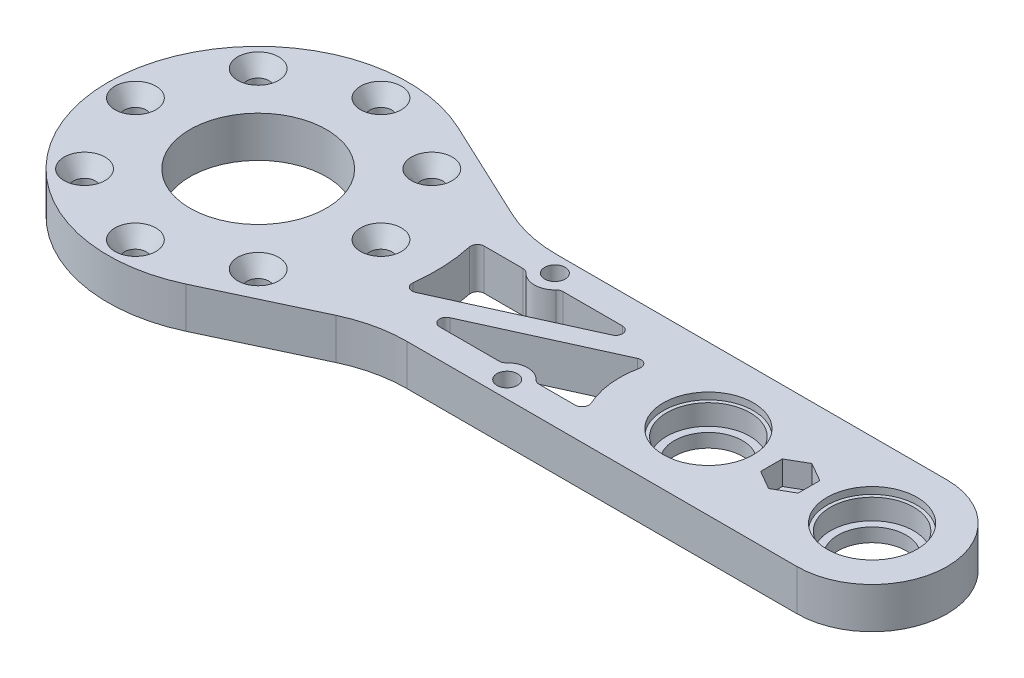
SolidWorks part; units mm, degrees
material "ABS"
ref_plane "前视基准面" through (0, 0, 0) normal (0, 0, 1) x (1, 0, 0)
ref_plane "上视基准面" through (0, 0, 0) normal (0, 1, 0) x (1, 0, 0)
ref_plane "右视基准面" through (0, 0, 0) normal (1, 0, 0) x (0, 0, -1)
other "Configuration Table"
sketch "草图1" plane through (0, 0, 0) normal (0, 1, 0) x (1, 0, 0)
  line L0 (0, 0) -> (-100, 0) construction
  line L1 (-100, -18) -> (-100, 18) construction
  line L2 (-10, -11) -> (-80.9474, -11)
  line L3 (-10, -11) -> (-10, 11) construction
  line L5 (-10, 11) -> (-80.9474, 11)
  line L7 (-74.8942, -6.76) -> (-45.1042, -6.76)
  line L12 (-74.8942, 6.76) -> (-45.1042, 6.76)
  line L13 (-74.8942, -6.76) -> (-45.1042, 6.76) construction
  line L14 (-74.2743, -8.1259) -> (-44.4843, 5.3941)
  line L15 (-75.5141, -5.3941) -> (-45.7241, 8.1259)
  circle A0 centre (-10, 0) radius 5
  circle A1 centre (-34, 0) radius 5
  circle A2 centre (-34, 0) radius 5 construction
  arc A3 (-5, 0) -> (-15, 0) centre (-10, 0) ccw construction
  circle A4 centre (-100, 0) radius 22
  circle A5 centre (-100, 0) radius 18 construction
  circle A6 centre (-100, 18) radius 1.6
  circle A7 centre (-87.2721, 12.7279) radius 1.6
  circle A8 centre (-82, 0) radius 1.6
  circle A9 centre (-87.2721, -12.7279) radius 1.6
  circle A10 centre (-100, -18) radius 1.6
  circle A11 centre (-112.7279, -12.7279) radius 1.6
  circle A12 centre (-118, 0) radius 1.6
  circle A13 centre (-112.7279, 12.7279) radius 1.6
  circle A14 centre (-100, 0) radius 10
  circle A15 centre (-34, 0) radius 9 construction
  arc A16 (-10, -11) -> (-10, 11) centre (-10, 0) ccw
  arc A20 (-74.8942, -6.76) -> (-74.8942, 6.76) centre (-100, 0) ccw
  arc A21 (-45.1042, 6.76) -> (-45.1042, -6.76) centre (-34, 0) ccw
  point P8 (-50, 0)
  point P31 (-100, 0)
  dimension "D2" = 10
  dimension "D3" = 10
  dimension "D4" = 24
  dimension "D6" = 44
  dimension "D7" = 36
  dimension "D8" = 3.2
  dimension "D10" = 20
  dimension "D11" = 18
  dimension "D12" = 22
  dimension "D13" = 50
  dimension "D14" = 4.24
  dimension "D15" = 4.24
  dimension "D16" = 52
  dimension "D17" = 26
  dimension "D18" = 1.5
  dimension "D1" = 100
  dimension "D5" = 10
  dimension "D19" = 1.5
  dimension "D9" = 8
extrude "凸台-拉伸1" add sketch "草图1" along normal blind 6
fillet "圆角1" radius 20 2 edges at (-80.9474, 3, -11) (-80.9474, 3, 11)
fillet "圆角2" radius 1 6 edges at (-45.1042, 3, 6.76) (-46.1433, 3, -4.6411) (-71.2646, 3, 6.76) (-74.8942, 3, -6.76) (-48.7337, 3, -6.76) (-74.4698, 3, 4.9201)
sketch "草图2" plane through (0, 0, 0) normal (0, -1, 0) x (1, 0, 0)
  circle A0 centre (-34, 0) radius 6.6
  circle A1 centre (-10, 0) radius 6.6
  dimension "D1" = 13.2
extrude "切除-拉伸2" cut sketch "草图2" along normal blind 5 from surface at -6 starting at face at (-53.6395, 6, 2.9007)
sketch "草图3" plane through (0, 6, 0) normal (0, 1, 0) x (1, 0, 0)
  line L0 (-10, 0) -> (-65, 0) construction
  line L1 (-65, 0) -> (-65, 8.5) construction
  line L2 (-65, 0) -> (-65, -8.5) construction
  line L3 (-73.6216, 6.76) -> (-53.3568, 6.76) construction
  line L4 (-57.4438, 6.76) -> (-52.5562, 6.76) construction
  circle A0 centre (-65, 8.5) radius 1.5
  circle A1 centre (-65, -8.5) radius 1.5 construction
  circle A2 centre (-55, 8.5) radius 1.5 construction
  arc A3 (-57.4438, 6.76) -> (-52.5562, 6.76) centre (-55, 8.5) ccw construction
  circle A4 centre (-55, -8.5) radius 1.5
  dimension "D3" = 8.5
  dimension "D5" = 2
  dimension "D4" = 3
  dimension "D7" = 6
  dimension "D1" = 55
  dimension "D2" = 8.5
  dimension "D6" = 10
extrude "切除-拉伸3" cut sketch "草图3" against normal blind 34
sketch "草图4" plane through (0, 6, 0) normal (0, 1, 0) x (1, 0, 0)
  line L0 (-71.6627, 11) -> (-90.6504, 19.9145)
  line L1 (-71.6627, -11) -> (-90.6504, -19.9145)
  arc A0 (-85.1567, 16.2381) -> (-85.1567, -16.2381) centre (-100, 0) ccw construction
  arc A1 (-85.1567, 16.2381) -> (-71.6627, 11) centre (-71.6627, 31) ccw construction
  arc A2 (-85.1567, 16.2381) -> (-90.6504, 19.9145) centre (-100, 0) ccw
  arc A3 (-85.1567, 16.2381) -> (-71.6627, 11) centre (-71.6627, 31) ccw
  arc A4 (-71.6627, -11) -> (-85.1567, -16.2381) centre (-71.6627, -31) ccw construction
  arc A5 (-71.6627, -11) -> (-85.1567, -16.2381) centre (-71.6627, -31) ccw
  arc A6 (-90.6504, -19.9145) -> (-85.1567, -16.2381) centre (-100, 0) ccw
extrude "凸台-拉伸2" add sketch "草图4" against normal up to surface (6 mm away) up to face at (-65, 0, -7)
fillet "圆角3" radius 20 2 edges at (-71.6627, 3, -11) (-71.6627, 3, 11)
sketch "草图5" plane through (0, 6, 0) normal (0, 1, 0) x (1, 0, 0)
  line L2 (-66.6415, -6.76) -> (-46.7602, -6.76) construction
  line L3 (-57.4438, -6.76) -> (-52.5562, -6.76)
  arc A1 (-52.5562, -6.76) -> (-57.4438, -6.76) centre (-55, -8.5) ccw
  dimension "D1" = 6
extrude "凸台-拉伸4" add sketch "草图5" against normal up to surface (6 mm away) up to face at (-63.4581, 0, 0)
fillet "圆角5" radius 1 2 edges at (-57.4438, 3, 6.76) (-52.5562, 3, 6.76)
sketch "草图6" plane through (0, 6, 0) normal (0, 1, 0) x (1, 0, 0)
  line L0 (-73.6216, 6.76) -> (-53.3568, 6.76) construction
  line L1 (-67.4438, 6.76) -> (-62.5562, 6.76)
  arc A0 (-67.4438, 6.76) -> (-62.5562, 6.76) centre (-65, 8.5) ccw
  dimension "D1" = 6
extrude "凸台-拉伸5" add sketch "草图6" against normal up to surface (6 mm away) up to face at (-63.4581, 0, 0)
fillet "圆角6" radius 1 2 edges at (-62.5562, 3, -6.76) (-67.4438, 3, -6.76)
sketch "草图7" plane through (0, 6, 0) normal (0, 1, 0) x (1, 0, 0)
  circle A0 centre (-10, 0) radius 6.6 construction
  circle A1 centre (-34, 0) radius 6.6 construction
  circle A2 centre (-10, 0) radius 6.6
  circle A3 centre (-34, 0) radius 6.6
  circle A4 centre (-10, 0) radius 5 construction
  circle A5 centre (-34, 0) radius 5 construction
  circle A6 centre (-10, 0) radius 5
  circle A7 centre (-34, 0) radius 5
extrude "凸台-拉伸6" add sketch "草图7" against normal up to surface (5 mm away) up to face at (-34, 1, 5)
sketch "草图8" plane through (0, 6, 0) normal (0, 1, 0) x (1, 0, 0)
  circle A0 centre (-34, 0) radius 6.6
  circle A1 centre (-10, 0) radius 6.6
  dimension "D1" = 13.2
extrude "切除-拉伸4" cut sketch "草图8" against normal blind 1
sketch "草图9" plane through (0, 5, 0) normal (0, 1, 0) x (1, 0, 0)
  circle A0 centre (-34, 0) radius 6.1
  circle A3 centre (-10, 0) radius 6.1
  dimension "D1" = 12.2
extrude "切除-拉伸5" cut sketch "草图9" against normal blind 3
sketch "草图10" plane through (0, 6, 0) normal (0, 1, 0) x (1, 0, 0)
  line L0 (-10, 0) -> (-34, 0) construction
  line L2 (-19.25, -1.5877) -> (-19.25, 1.5877)
  line L3 (-19.25, 1.5877) -> (-22, 3.1754)
  line L4 (-22, 3.1754) -> (-24.75, 1.5877)
  line L5 (-24.75, 1.5877) -> (-24.75, -1.5877)
  line L6 (-24.75, -1.5877) -> (-22, -3.1754)
  line L7 (-22, -3.1754) -> (-19.25, -1.5877)
  circle A0 centre (-22, 0) radius 2.75 construction
  dimension "D1" = 5.5
extrude "切除-拉伸6" cut sketch "草图10" against normal blind 3.5
sketch "草图11" plane through (0, 2.5, 0) normal (0, 1, 0) x (1, 0, 0)
  line L0 (-34, 0) -> (-10, 0) construction
  circle A0 centre (-22, 0) radius 1.5
  dimension "D1" = 3
extrude "切除-拉伸7" cut sketch "草图11" against normal blind 3.5
sketch "草图12" plane through (0, 6, 0) normal (0, 1, 0) x (1, 0, 0)
  line L0 (-100, -18) -> (-100, 18) construction
sketch "草图13" plane through (0, 0, 0) normal (0, 0, 1) x (1, 0, 0)
  line L0 (-100, 6) -> (-100, 0) construction
  line L1 (-98.4, 6) -> (-101.6, 6) construction
  line L2 (-122, 0) -> (-90.6504, 0) construction
ref_plane "基准面1" through (-100, 0, 0) normal (-1, 0, 0) x (0, 0, 1)
sketch "草图15" plane through (-100, 0, 0) normal (-1, 0, 0) x (0, 0, 1)
  line L0 (-18, 0) -> (-18, 6) construction
  line L1 (-22, 0) -> (22, 0) construction
  line L2 (18, 6) -> (-18, 6) construction
  line L3 (-21, 6) -> (-19.5, 3.5)
  line L4 (-19.5, 3.5) -> (-19.5, 0)
  line L5 (-19.5, 0) -> (-18, 0)
  line L6 (-18, 0) -> (-18, 6)
  line L7 (-18, 6) -> (-21, 6)
  line L8 (0, 6) -> (0, 0) construction
  dimension "D1" = 2.5
  dimension "D2" = 3
  dimension "D3" = 1.5
  dimension "D4" = 18
revolve "切除-旋转1" cut sketch "草图15" angle 360 about L0
pattern_circular "阵列(圆周)1" count 8 over 360 about axis through (-100, 0, 0) along (0, 1, 0) of "切除-旋转1"
